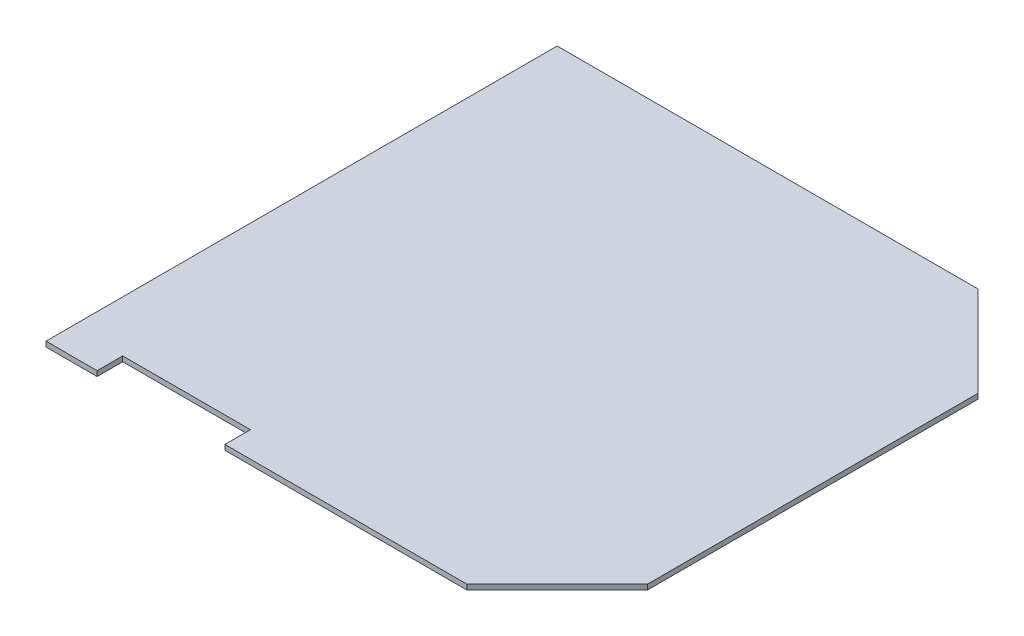
SolidWorks part; units mm, degrees
ref_plane "Front Plane" through (0, 0, 0) normal (0, 0, 1) x (1, 0, 0)
ref_plane "Top Plane" through (0, 0, 0) normal (0, 1, 0) x (1, 0, 0)
ref_plane "Right Plane" through (0, 0, 0) normal (1, 0, 0) x (0, 0, -1)
sketch "Sketch1" plane through (0, 0, 0) normal (0, 1, 0) x (1, 0, 0)
  line L0 (-82.3223, 100) -> (82.3223, 100)
  line L1 (82.3223, 100) -> (117.6777, 64.6447)
  line L2 (117.6777, 64.6447) -> (117.6777, -64.6447)
  line L3 (117.6777, -64.6447) -> (82.3223, -100)
  line L9 (-82.3223, -100) -> (-82.3223, 100)
  line L10 (-82.3223, -100) -> (82.3223, -100)
  point P9 (-82.3223, 0)
  point P11 (0, 100)
  point P14 (117.6777, 0)
  dimension "D1" = 200
  dimension "D2" = 200
  dimension "D3" = 45
  dimension "D4" = 45
  dimension "D5" = 50
extrude "Boss-Extrude1" add sketch "Sketch1" along normal blind 2
sketch "Sketch2" plane through (0, 2, 0) normal (0, 1, 0) x (1, 0, 0)
  line L0 (-82.3223, -100) -> (82.3223, -100) construction
  line L1 (-62.3223, -100) -> (-12.3223, -100)
  line L2 (-62.3223, -100) -> (-62.3223, -90)
  line L3 (-62.3223, -90) -> (-12.3223, -90)
  line L4 (-12.3223, -100) -> (-12.3223, -90)
  line L5 (-82.3223, 100) -> (-82.3223, -100) construction
  dimension "D1" = 10
  dimension "D2" = 50
  dimension "D3" = 20
extrude "Cut-Extrude1" cut sketch "Sketch2" against normal through all
